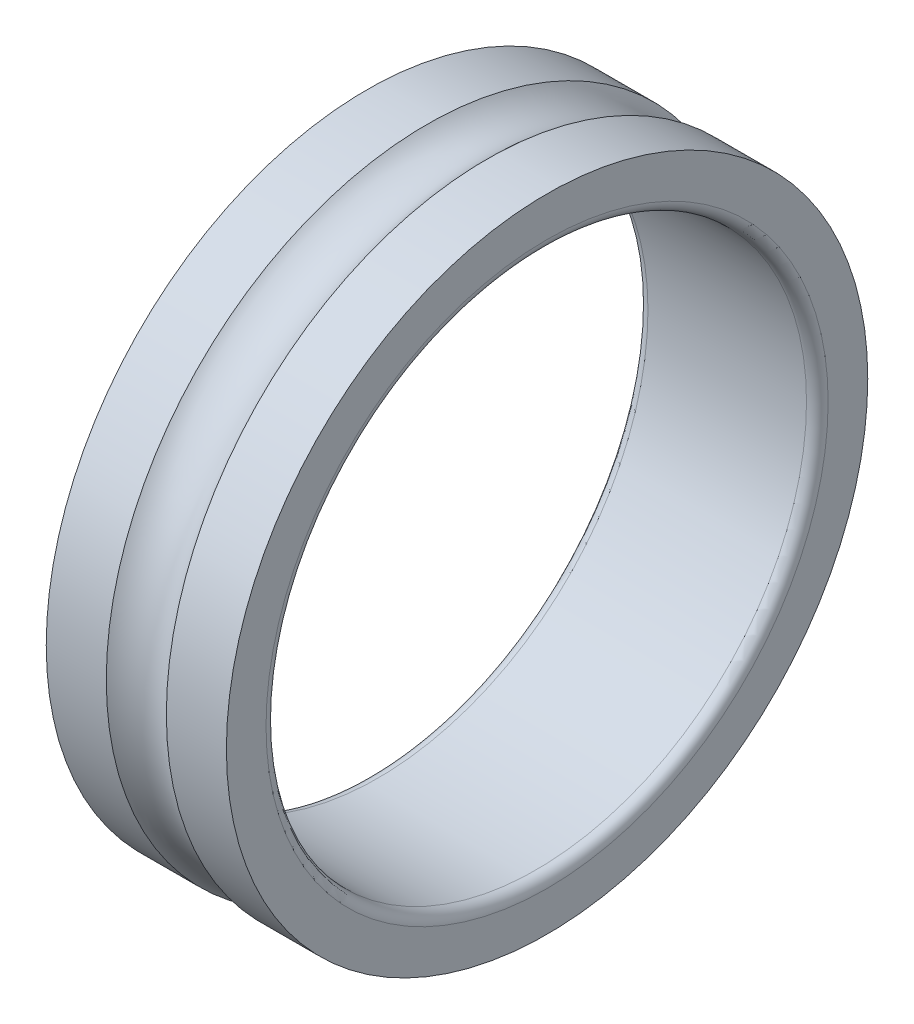
SolidWorks part; units mm, degrees
ref_plane "Front Plane" through (0, 0, 0) normal (0, 0, 1) x (1, 0, 0)
ref_plane "Top Plane" through (0, 0, 0) normal (0, 1, 0) x (1, 0, 0)
ref_plane "Right Plane" through (0, 0, 0) normal (1, 0, 0) x (0, 0, -1)
ref_plane "Plane1"
sketch "Sketch1" plane through (0, 0, 0) normal (0, 0, 1) x (1, 0, 0)
  line L0 (0.3, 7.5) -> (4.7, 7.5)
  line L1 (5, 7.8) -> (5, 8.9)
  line L2 (5, 8.9) -> (3.3335, 8.9)
  line L3 (1.6665, 8.9) -> (0, 8.9)
  line L4 (0, 8.9) -> (0, 7.8)
  line L5 (50, 0) -> (-50, 0) construction
  arc A0 (0, 7.8) -> (0.3, 7.5) centre (0.3, 7.8) ccw
  arc A1 (4.7, 7.5) -> (5, 7.8) centre (4.7, 7.8) ccw
  arc A2 (1.6665, 8.9) -> (3.3335, 8.9) centre (2.5, 9.75) ccw
revolve "Revolução1" add sketch "Sketch1" angle 360 about L5
